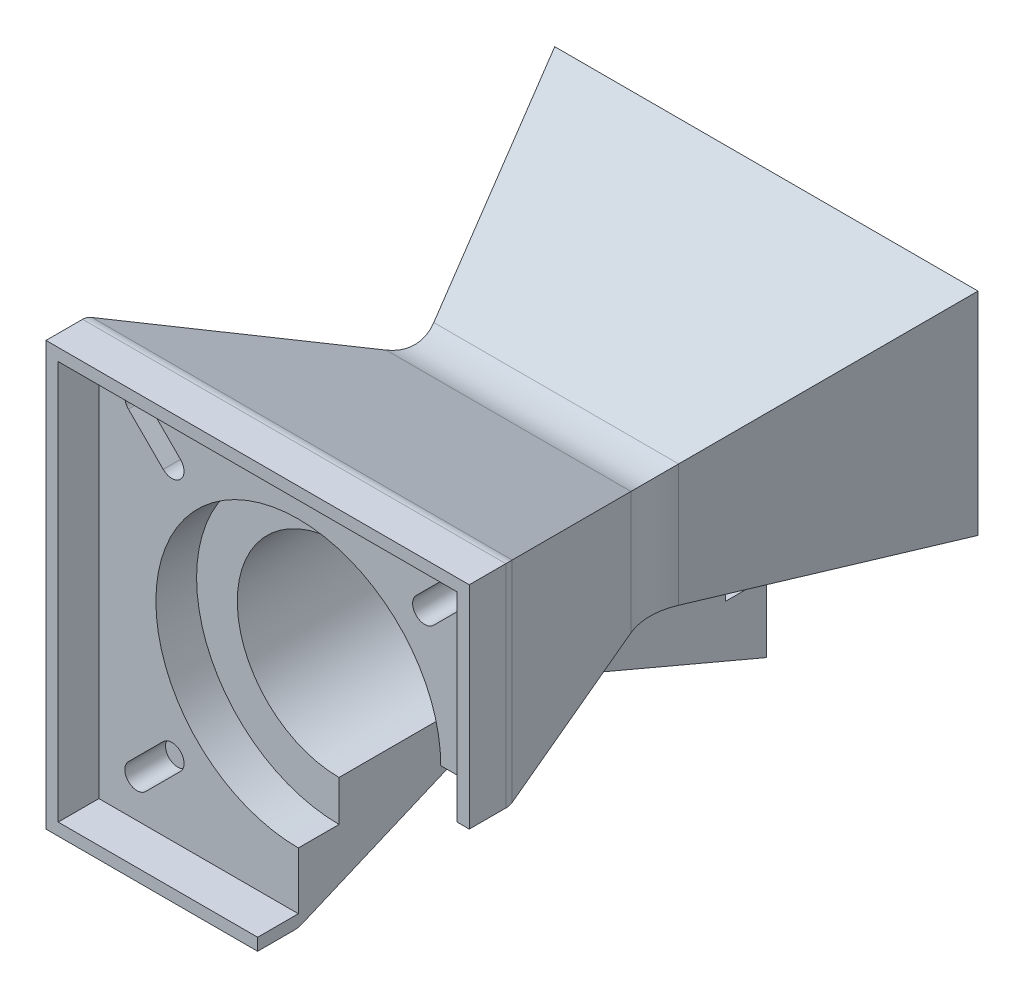
SolidWorks part; units mm, degrees
material "Cast Stainless Steel"
ref_plane "Front Plane" through (0, 0, 0) normal (0, 0, 1) x (1, 0, 0)
ref_plane "Top Plane" through (0, 0, 0) normal (0, 1, 0) x (1, 0, 0)
ref_plane "Right Plane" through (0, 0, 0) normal (1, 0, 0) x (0, 0, -1)
sketch "Sketch1" plane through (0, 0, 0) normal (0, 0, 1) x (1, 0, 0)
  line L0 (0, 0) -> (104, 0)
  line L1 (104, 0) -> (104, 104)
  line L2 (104, 104) -> (0, 104)
  line L3 (0, 104) -> (0, 0)
  dimension "D1" = 104
  dimension "D2" = 104
extrude "Boss-Extrude1" add sketch "Sketch1" along normal blind 57.5 draft 23
mirror "Mirror1" about plane through (0, 0, 57.5) normal (0, 0, 1) of "Boss-Extrude1"
sketch "Sketch2" plane through (0, 0, 115) normal (0, 0, 1) x (1, 0, 0)
  line L0 (0, 52) -> (104, 52) construction
  line L1 (0, 104) -> (0, 0) construction
  line L2 (104, 0) -> (104, 104) construction
  circle A0 centre (52, 52) radius 25
  dimension "D1" = 50
extrude "Cut-Extrude1" cut sketch "Sketch2" against normal through all
sketch "Sketch3" plane through (0, 0, 115) normal (0, 0, 1) x (1, 0, 0)
  line L0 (104, 52) -> (0, 52) construction
  line L1 (104, 0) -> (104, 104) construction
  line L2 (0, 104) -> (0, 0) construction
  line L3 (52, 104) -> (52, 0) construction
  line L4 (104, 104) -> (0, 104) construction
  line L5 (0, 0) -> (104, 0) construction
  line L6 (52, 0) -> (104, 0)
  line L7 (104, 0) -> (104, 52)
  circle A0 centre (52, 52) radius 35
  circle M1 centre (52, 52) radius 25
  dimension "D1" = 70
extrude "Cut-Extrude2" cut sketch "Sketch3" against normal blind 10 contours A0 M1
sketch "Sketch4" plane through (0, 0, 0) normal (0, 0, -1) x (-1, 0, 0)
  circle A0 centre (-52, 52) radius 35
  dimension "D1" = 70
extrude "Cut-Extrude3" cut sketch "Sketch4" against normal blind 10
sketch "Sketch5" plane through (0, 0, 115) normal (0, 0, 1) x (1, 0, 0)
  line L0 (52, 0) -> (52, 52)
  line L2 (104, 0) -> (104, 104) construction
  line L3 (52, 52) -> (104, 52)
  line L5 (0, 0) -> (104, 0) construction
  line L6 (52, 0) -> (104, 0)
  line L7 (104, 0) -> (104, 52)
extrude "Cut-Extrude4" cut sketch "Sketch5" against normal through all
fillet "Fillet1" radius 15 4 edges at (79.5927, 65.7963, 57.5) (52, 79.5927, 57.5) (24.4073, 52, 57.5) (38.2037, 24.4073, 57.5)
sketch "Sketch6" plane through (0, 0, 115) normal (0, 0, 1) x (1, 0, 0)
  line L0 (52, 3) -> (3, 3)
  line L1 (52, 17) -> (52, 0) construction
  line L2 (3, 3) -> (3, 101)
  line L3 (3, 101) -> (101, 101)
  line L4 (101, 101) -> (101, 52)
  line L5 (104, 52) -> (87, 52) construction
  line L6 (104, 52) -> (104, 104) construction
  line L7 (104, 104) -> (0, 104) construction
  line L8 (0, 104) -> (0, 0) construction
  line L9 (0, 0) -> (52, 0) construction
  line L16 (0, 0) -> (52, 0)
  line L17 (52, 0) -> (52, 17)
  line L18 (87, 52) -> (104, 52)
  line L19 (104, 52) -> (104, 104)
  line L20 (104, 104) -> (0, 104)
  line L21 (0, 104) -> (0, 0)
  line L23 (52, 3) -> (52, 17)
  line L24 (87, 52) -> (101, 52)
  arc A1 (87, 52) -> (52, 17) centre (52, 52) ccw
  arc A2 (87, 52) -> (52, 17) centre (52, 52) ccw
  line M12 (0, 0) -> (52, 0)
  line M13 (52, 0) -> (52, 17)
  line M15 (87, 52) -> (104, 52)
  line M16 (104, 52) -> (104, 104)
  line M17 (104, 104) -> (0, 104)
  line M18 (0, 104) -> (0, 0)
  dimension "D1" = 3
  dimension "D2" = 3
  dimension "D3" = 3
  dimension "D4" = 3
  dimension "D5" = 0
extrude "Boss-Extrude2" add sketch "Sketch6" along normal blind 10 contours L3 L4 L0 L2 M15 M16 M17 M18 M12 M13
sketch "Sketch7" plane through (0, 0, 115) normal (0, 0, 1) x (1, 0, 0)
  line L0 (104, 52) -> (0, 52) construction
  line L1 (0, 104) -> (0, 0) construction
  line L2 (52, 101) -> (52, 52) construction
  line L3 (3, 101) -> (101, 101) construction
  line L4 (52, 52) -> (52, 0) construction
  line L5 (52, 52) -> (3, 101) construction
  line L6 (20.917, 83.083) -> (12.3723, 91.6277) construction
  line L7 (18.7957, 80.9617) -> (10.251, 89.5063)
  line L8 (23.0383, 85.2043) -> (14.4937, 93.749)
  line L9 (20.917, 20.917) -> (12.3723, 12.3723) construction
  line L10 (18.7957, 23.0383) -> (10.251, 14.4937)
  line L11 (23.0383, 18.7957) -> (14.4937, 10.251)
  line L12 (83.083, 83.083) -> (91.6277, 91.6277) construction
  line L13 (85.2043, 80.9617) -> (93.749, 89.5063)
  line L14 (80.9617, 85.2043) -> (89.5063, 93.749)
  circle A0 centre (52, 52) radius 50
  arc A1 (18.7957, 80.9617) -> (23.0383, 85.2043) centre (20.917, 83.083) ccw
  arc A2 (14.4937, 93.749) -> (10.251, 89.5063) centre (12.3723, 91.6277) ccw
  arc A3 (18.7957, 23.0383) -> (23.0383, 18.7957) centre (20.917, 20.917) cw
  arc A4 (14.4937, 10.251) -> (10.251, 14.4937) centre (12.3723, 12.3723) cw
  arc A5 (85.2043, 80.9617) -> (80.9617, 85.2043) centre (83.083, 83.083) cw
  arc A6 (89.5063, 93.749) -> (93.749, 89.5063) centre (91.6277, 91.6277) cw
  point P17 (16.6447, 87.3553)
  point P22 (0, 0)
  point P24 (16.6447, 16.6447)
  point P31 (87.3553, 87.3553)
  dimension "D1" = 100
  dimension "D2" = 3
  dimension "D3" = 12.0839
extrude "Cut-Extrude5" cut sketch "Sketch7" against normal blind 10 contours L8 A2 L7 A0 | L7 A1 L8 A0 | A4 L11 A0 L10 | A3 L10 A0 L11 | A5 L13 A0 L14 | A6 L14 A0 L13
fillet "Fillet2" radius 5 4 edges at (104, 78, 115) (52, 104, 115) (0, 52, 115) (26, 0, 115)
equation "\"a\" = 115mm"
equation "\"b\"= 104mm"
equation "\"c\" = 23deg"
